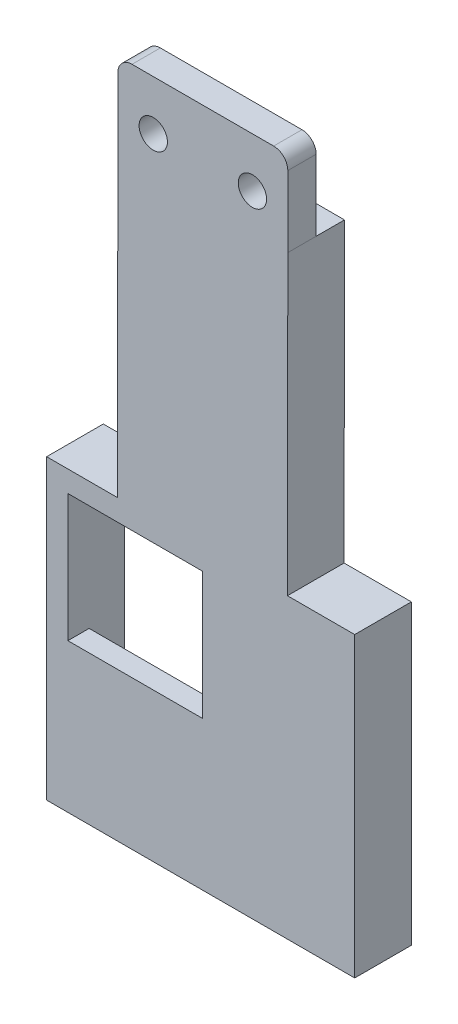
SolidWorks part; units mm, degrees
ref_plane "前视基准面" through (0, 0, 0) normal (0, 0, 1) x (1, 0, 0)
ref_plane "上视基准面" through (0, 0, 0) normal (0, 1, 0) x (1, 0, 0)
ref_plane "右视基准面" through (0, 0, 0) normal (1, 0, 0) x (0, 0, -1)
other "Configuration Table"
sketch "草图1" plane through (0, 0, 0) normal (0, 0, 1) x (1, 0, 0)
  line L0 (49.5832, -14) -> (49.5832, -28)
  line L1 (49.5832, -24) -> (49.5832, -9) construction
  line L2 (49.5832, -28) -> (25.5832, -28)
  line L3 (25.5832, -28) -> (25.5832, -14)
  line L4 (25.5832, -24) -> (25.5832, -9) construction
  line L5 (27.5832, -12) -> (47.5832, -12)
  line L6 (25.5832, -12) -> (49.5832, -12) construction
  line L7 (49.5832, -24) -> (25.5832, -24) construction
  line L8 (49.8934, -24.0299) -> (25.5832, -24)
  circle A0 centre (44.5832, -19) radius 2 construction
  circle A1 centre (44.5832, -19) radius 2
  circle A2 centre (30.5832, -19) radius 2 construction
  circle A3 centre (30.5832, -19) radius 2
  arc A4 (25.5832, -14) -> (27.5832, -12) centre (27.5832, -14) cw
  arc A5 (49.5832, -14) -> (47.5832, -12) centre (47.5832, -14) ccw
  point P23 (25.5832, -12)
  point P26 (49.5832, -12)
  dimension "D2" = 2
  dimension "D1" = 4
extrude "凸台-拉伸1" add sketch "草图1" along normal blind 4 contours L0 A5 L5 A4 L3 L8 A1 A3
sketch "草图2" plane through (-0.0295, -23.9685, 0) normal (-0.0012, -1, 0) x (1, -0.0012, 0)
  line L0 (25.6127, 4) -> (25.6127, -4)
  line L1 (25.6127, -4) -> (49.6127, -4)
  line L3 (25.6127, 4) -> (49.6127, 4)
  line L4 (49.6127, 4) -> (49.6127, -4)
  line L5 (49.6127, -4) -> (49.5979, -4) construction
  point P10 (49.5923, -4)
extrude "凸台-拉伸2" add sketch "草图2" along normal blind 45
sketch "草图3" plane through (0, 0, 4) normal (0, 0, 1) x (1, 0, 0)
  line L0 (37.5279, -69.0147) -> (18.5279, -69.0147)
  line L1 (18.5279, -69.0147) -> (18.5279, -105.0147)
  line L2 (18.5279, -105.0147) -> (37.0279, -105.0147)
  line L3 (37.5512, -44.1398) -> (37.5512, -56.043) construction
  line L4 (37.5279, -66.0147) -> (15.5279, -66.0147)
  line L5 (15.5279, -66.0147) -> (15.5279, -108.0147)
  line L6 (49.5279, -69.0295) -> (49.5832, -24.0295) construction
  line L7 (37.5279, -69.0147) -> (56.0279, -69.0147)
  line L8 (49.5279, -69.0295) -> (25.5279, -69) construction
  line L9 (56.0279, -69.0147) -> (56.0279, -105.0147)
  line L10 (56.0279, -105.0147) -> (37.0279, -105.0147)
  line L11 (15.5279, -108.0147) -> (37.0279, -108.0147)
  line L12 (59.0279, -108.0147) -> (37.0279, -108.0147)
  line L13 (59.0279, -66.0147) -> (59.0279, -108.0147)
  line L14 (37.5279, -66.0147) -> (59.0279, -66.0147)
  point P0 (37.5512, -50.0914)
  dimension "D1" = 12
  dimension "D3" = 36
  dimension "D4" = 19
  dimension "D2" = 18.5
  dimension "D5" = 19
  dimension "D6" = 3
extrude "凸台-拉伸3" add sketch "草图3" against normal blind 5 from offset 3 offset against normal yes
sketch "草图4" plane through (0, 0, 1) normal (0, 0, 1) x (1, 0, 0)
  line L0 (15.5279, -66.0147) -> (15.5279, -108.0147)
  line L1 (15.5279, -108.0147) -> (59.0279, -108.0147)
  line L2 (59.0279, -108.0147) -> (59.0279, -66.0147)
  line L3 (59.0279, -66.0147) -> (15.5279, -66.0147)
  line L4 (37.5279, -69.0147) -> (37.5279, -87.0147)
  line L5 (49.5279, -69.0295) -> (25.5279, -69) construction
  line L6 (37.5279, -87.0147) -> (18.5279, -87.0147)
  line L7 (18.5279, -69.0147) -> (18.5279, -105.0147) construction
  line L8 (18.5279, -87.0147) -> (18.5279, -69.0147)
  line L9 (18.5279, -69.0147) -> (37.5279, -69.0147)
extrude "凸台-拉伸4" add sketch "草图4" along normal blind 3
